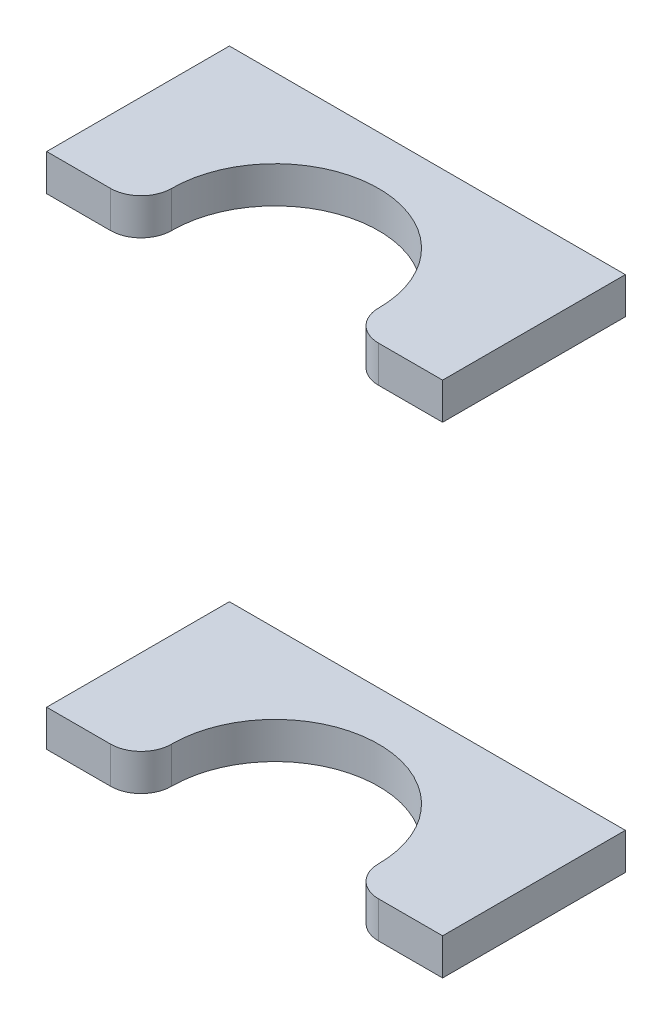
SolidWorks part; units mm, degrees
material "Plain Carbon Steel"
ref_plane "Front Plane" through (0, 0, 0) normal (0, 0, 1) x (1, 0, 0)
ref_plane "Top Plane" through (0, 0, 0) normal (0, 1, 0) x (1, 0, 0)
ref_plane "Right Plane" through (0, 0, 0) normal (1, 0, 0) x (0, 0, -1)
sketch "Sketch1" plane through (0, 0, 0) normal (0, 0, 1) x (1, 0, 0)
  line L0 (-351.5, 0) -> (-351.5, 125) construction
  line L1 (675, 0) -> (-675, 0) construction
  line L2 (-675, 125) -> (675, 125) construction
  line L3 (-351.5, 62.5) -> (-213.0727, 62.5) construction
  line L4 (-319, 20) -> (-384, 20)
  line L5 (-319, 20) -> (-319, 26)
  line L6 (-319, 26) -> (-384, 26)
  line L7 (-384, 20) -> (-384, 26)
  line L8 (-319, 20) -> (-384, 26) construction
  line L9 (-319, 26) -> (-384, 20) construction
  line L10 (-319, 99) -> (-384, 105) construction
  line L11 (-319, 105) -> (-384, 99) construction
  line L12 (-384, 105) -> (-384, 99)
  line L13 (-319, 99) -> (-384, 99)
  line L14 (-319, 105) -> (-319, 99)
  line L15 (-319, 105) -> (-384, 105)
  line L16 (-424, 125) -> (-424, -339) construction
  point P6 (-351.5, 23)
  point P17 (-351.5, 102)
  dimension "D1" = 6
  dimension "D2" = 65
  dimension "D3" = 20
  dimension "D4" = 40
extrude "Boss-Extrude1" add sketch "Sketch1" along normal up to surface (44 mm away)
sketch "Sketch4" plane through (0, 20, 0) normal (0, -1, 0) x (-1, 0, 0)
  line L0 (424, -25) -> (319, -25) construction
  line L1 (424, -39) -> (424, -11) construction
  line L2 (319, -44) -> (319, 0) construction
  line L3 (351.5, -44) -> (351.5, -25) construction
  line L4 (384, -44) -> (319, -44) construction
  line L5 (319, -30) -> (319, -44)
  line L6 (384, -30) -> (384, -44)
  line L7 (384, -44) -> (319, -44)
  line L9 (373.5, -30) -> (384, -30)
  line L12 (329.5, -30) -> (319, -30)
  arc A0 (368.5, -25) -> (334.5, -25) centre (351.5, -25) ccw
  arc A1 (368.5, -25) -> (373.5, -30) centre (373.5, -25) ccw
  arc A2 (334.5, -25) -> (329.5, -30) centre (329.5, -25) cw
  dimension "D1" = 34
  dimension "D2" = 5
extrude "Cut-Extrude4" cut sketch "Sketch4" against normal through all
